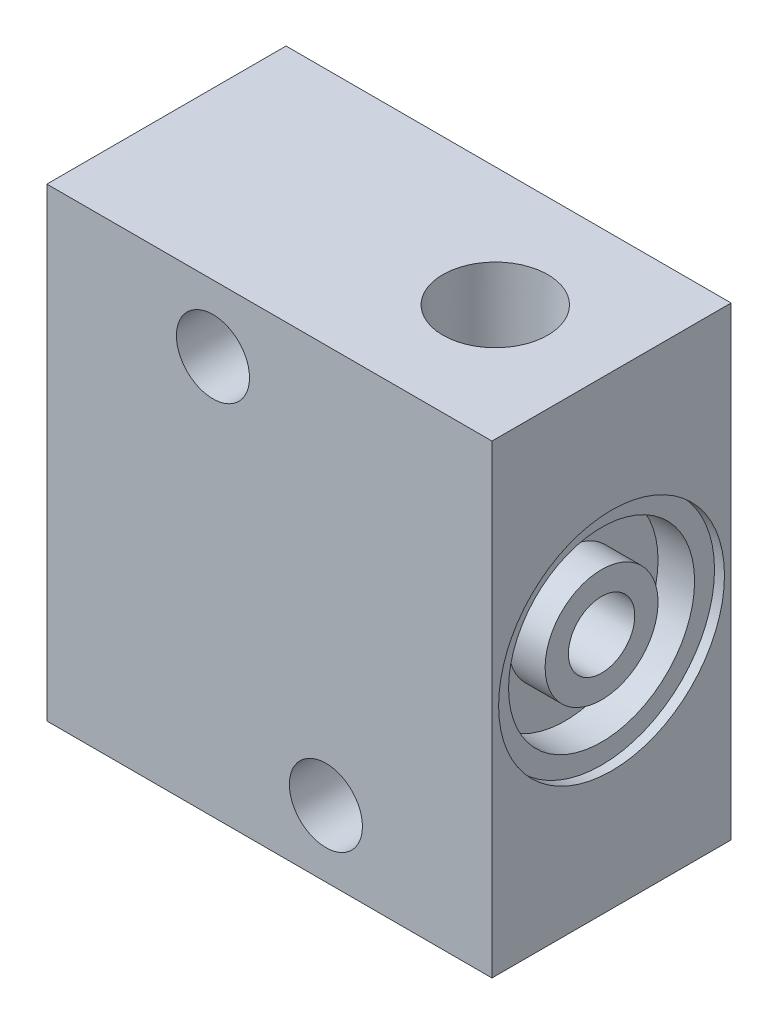
SolidWorks part; units mm, degrees
ref_plane "Plan médian de symétrie" through (0, 0, 0) normal (0, 0, 1) x (1, 0, 0)
ref_plane "Dessus" through (0, 0, 0) normal (0, 1, 0) x (1, 0, 0)
ref_plane "Plan d'assemblage chapeau" through (0, 0, 0) normal (1, 0, 0) x (0, 0, -1)
sketch "Esquisse1" plane through (0, 0, 0) normal (0, 0, 1) x (1, 0, 0)
  line L1 (0, 35) -> (67, 35)
  line L2 (0, 35) -> (0, -35)
  line L3 (0, -35) -> (67, -35)
  line L4 (67, 35) -> (67, -35)
  dimension "D1" = 67
  dimension "D2" = 70
extrude "Base-Extrusion" add sketch "Esquisse1" along normal mid plane 36
sketch "Esquisse2" plane through (0, 0, 0) normal (0, 0, 1) x (1, 0, 0)
  line L0 (-4.4411, 0) -> (72.225, 0) construction
  line L1 (0, 12.5) -> (12.5, 12.5)
  line L2 (0, 35) -> (0, -35) construction
  line L3 (12.5, 12.5) -> (12.5, 10)
  line L4 (12.5, 10) -> (11.75, 10)
  line L6 (11.75, 8.5) -> (12.25, 8.5)
  line L7 (12.25, 8.5) -> (12.75, 8)
  line L8 (12.75, 8) -> (20.5, 8)
  line L9 (20.5, 8) -> (21.5, 9)
  line L10 (21.5, 9) -> (28.5, 9)
  line L11 (28.5, 9) -> (29.5, 8)
  line L12 (29.5, 8) -> (45, 8)
  line L13 (54, 8) -> (54, 5)
  line L14 (54, 5) -> (65.5, 5)
  line L15 (65.5, 5) -> (65.5, 8.5)
  line L16 (65.5, 8.5) -> (60, 8.5)
  line L17 (60, 8.5) -> (60, 14)
  line L18 (60, 14) -> (65.5, 14)
  line L19 (65.5, 14) -> (65.5, 17)
  line L20 (65.5, 17) -> (67, 17)
  line L21 (67, -35) -> (67, 35) construction
  line L22 (67, 17) -> (67, 0)
  line L23 (0, 12.5) -> (0, 0)
  line L24 (25, 9) -> (25, 12.5) construction
  line L25 (49.5, 13.7797) -> (49.5, 3.7457) construction
  line L26 (45, 8) -> (45, 12)
  line L27 (45, 12) -> (54, 12)
  line L28 (54, 12) -> (54, 8)
  line L29 (0, 0) -> (67, 0)
  line L30 (11, 9.25) -> (12.894, 9.25) construction
  arc A0 (11.75, 10) -> (11.75, 8.5) centre (11.75, 9.25) ccw
  dimension "D17" = 1.5
  dimension "D1" = 12.5
  dimension "D2" = 5
  dimension "D3" = 8
  dimension "D4" = 9
  dimension "D5" = 8.5
  dimension "D6" = 10
  dimension "D7" = 9.25
  dimension "D8" = 12.5
  dimension "D9" = 11.75
  dimension "D10" = 45
  dimension "D11" = 7
  dimension "D12" = 45
  dimension "D13" = 45
  dimension "D14" = 25
  dimension "D15" = 54
  dimension "D16" = 10.034
  dimension "D18" = 12
  dimension "D19" = 4.5
  dimension "D20" = 4.5
  dimension "D21" = 8.5
  dimension "D22" = 14
  dimension "D23" = 17
  dimension "D24" = 1.5
  dimension "D25" = 6
  dimension "D26" = 0.5
revolve "Enlèvement de matière-Révolution1" cut sketch "Esquisse2" angle 360 about L0
hole_wizard "Filetage de tuyauterie ISO 7 - Rc 3/81" positions "Esquisse5" profile "Esquisse4" size "3/8" standard "ISO"
sketch "Esquisse5" plane through (0, 35, 0) normal (0, 1, 0) x (-1, 0, 0)
  point P0 (-49.5, 0)
  dimension "D1" = 49.5
sketch "Esquisse4" plane through (49.5, 35, 0) normal (1, 0, 0) x (0, 0, 1)
  line L0 (0, 0) -> (0, 26.2962)
  line L1 (7.15, 22) -> (0, 26.2962)
  line L2 (-7.15, 22) -> (0, 26.2962) construction
  line L3 (7.15, 22) -> (7.15, 20)
  line L4 (7.15, 20) -> (7.2787, 20)
  line L5 (7.2787, 20) -> (7.903, 0)
  line L6 (-7.2787, 20) -> (-7.903, 0) construction
  line L7 (7.903, 0) -> (0, 0)
  line L8 (0, -6.35) -> (0, 107.95) construction
  line L11 (-7.15, 20) -> (-7.2787, 20) construction
  dimension "Diamètre du trou pour taraudage" = 14.3
  dimension "Profondeur du trou pour taraudage" = 22
  dimension "Diamètre du filetage" = 15.806
  dimension "Angle de filetage" = 3.576
  dimension "Profondeur du filetage" = 20
  dimension "Angle de pointe" = 118
cosmetic thread "Représentation de filetage1" parameters "D1"=17
sketch "Esquisse6" plane through (82.7083, -35, -11.9178) normal (0, -1, 0) x (1, 0, 0)
  line L0 (-57.7083, 11.9178) -> (-82.7083, 11.9178) construction
  line L1 (-61.2083, 20.9178) -> (-54.2083, 20.9178) construction
  line L2 (-54.2083, 20.9178) -> (-61.2083, 20.9178) construction
  line L3 (-54.2083, 20.9178) -> (-54.2083, 2.9178) construction
  line L6 (-57.7083, 20.9178) -> (-57.7083, 6.6054) construction
  point P0 (-57.7083, 11.9178)
sketch "Esquisse7" plane through (25, -35, 0) normal (1, 0, 0) x (0, 0, -1)
  line L0 (0, 0) -> (0, 26.2962)
  line L1 (7.15, 22) -> (0, 26.2962)
  line L2 (-7.15, 22) -> (0, 26.2962) construction
  line L3 (7.15, 22) -> (7.15, 20)
  line L4 (7.15, 20) -> (7.2787, 20)
  line L5 (7.2787, 20) -> (7.903, 0)
  line L6 (-7.2787, 20) -> (-7.903, 0) construction
  line L7 (7.903, 0) -> (0, 0)
  line L8 (0, -6.35) -> (0, 107.95) construction
  line L11 (-7.15, 20) -> (-7.2787, 20) construction
  dimension "Diamètre du trou pour taraudage" = 14.3
  dimension "Profondeur du trou pour taraudage" = 22
  dimension "Diamètre du filetage" = 15.806
  dimension "Angle de filetage" = 3.576
  dimension "Profondeur du filetage" = 20
  dimension "Angle de pointe" = 118
hole_wizard "Perçage1" positions "Esquisse6" profile "Esquisse7" size "3/8" standard "ISO"
cosmetic thread "Représentation de filetage2" parameters "D1"=17
sketch "Esquisse8" plane through (0, -35, 0) normal (0, -1, 0) x (1, 0, 0)
  circle A0 centre (25, 0) radius 2.8512
extrude "Enlèv. mat.-Extru.1" cut sketch "Esquisse8" against normal blind 29
sketch "Esquisse9" plane through (0, 0, 18) normal (0, 0, 1) x (1, 0, 0)
  line L0 (0, 0) -> (57.6199, 0) construction
  line L1 (0, 35) -> (0, -35) construction
  line L2 (67, -35) -> (67, 35) construction
  circle A0 centre (25, 25) radius 5.5
  circle A1 centre (42, -25) radius 5.5
  dimension "D5" = 11
  dimension "D6" = 11
  dimension "D1" = 25
  dimension "D2" = 25
  dimension "D3" = 25
  dimension "D4" = 25
extrude "Trous de passage pour fixationmat.-Extru.2" cut sketch "Esquisse9" against normal through all
hole_wizard "Trou taraudé M5x0.81" positions "Esquisse11" profile "Esquisse10" tap size "M5x0.8" standard "ISO"
sketch "Esquisse11" plane through (0, 0, 0) normal (-1, 0, 0) x (0, 0, 1)
  line L0 (0, 0) -> (0, 39.0241) construction
  point P0 (7.5, 25)
  dimension "D1" = 7.5
  dimension "D2" = 25
sketch "Esquisse10" plane through (0, 25, 7.5) normal (0, 1, 0) x (0, 0, 1)
  line L0 (0, 0) -> (0, 15.2618)
  line L1 (0, 15.2618) -> (2.1, 14)
  line L2 (2.1, 14) -> (2.1, 0)
  line L5 (2.1, 0) -> (0, 0)
  line L10 (0, 15.2618) -> (-2.1, 14) construction
  line L11 (0, -6.35) -> (0, 107.95) construction
  dimension "Diamètre du trou pour taraudage" = 4.2
  dimension "Profondeur du trou pour taraudage" = 14
  dimension "Angle de pointe" = 118
cosmetic thread "Représentation de filetage4" parameters "D1"=13, "D2"=5
pattern_linear "Répétition linéaire1" count 2 spacing 15 along (0, 0, -1) count 2 spacing 50 along (0, -1, 0) of "Trou taraudé M5x0.81"
hole_wizard "Trou taraudé M5x0.82" positions "Esquisse13" profile "Esquisse12" tap size "M5x0.8" standard "ISO"
sketch "Esquisse13" plane through (0, -35, 0) normal (0, -1, 0) x (1, 0, 0)
  line L0 (67, 18) -> (67, -18) construction
  line L1 (0, 0) -> (67.9389, 0) construction
  point P0 (54, -7.5)
  dimension "D1" = 13
  dimension "D2" = 7.5
sketch "Esquisse12" plane through (54, -35, -7.5) normal (1, 0, 0) x (0, 0, -1)
  line L0 (0, 0) -> (0, 19.2618)
  line L1 (0, 19.2618) -> (2.1, 18)
  line L2 (2.1, 18) -> (2.1, 0)
  line L5 (2.1, 0) -> (0, 0)
  line L10 (0, 19.2618) -> (-2.1, 18) construction
  line L11 (0, -6.35) -> (0, 107.95) construction
  dimension "Diamètre du perçage" = 4.2
  dimension "Profondeur du perçage" = 18
  dimension "Angle de pointe" = 118
cosmetic thread "Représentation de filetage5" parameters "D1"=16, "D2"=5
mirror "Symétrie1" about plane through (0, 0, 0) normal (0, 0, 1) of "Trou taraudé M5x0.82"
ref_plane "Plan assemblage soupape" through (11, 0, 0) normal (-1, 0, 0) x (0, 0, 1)
